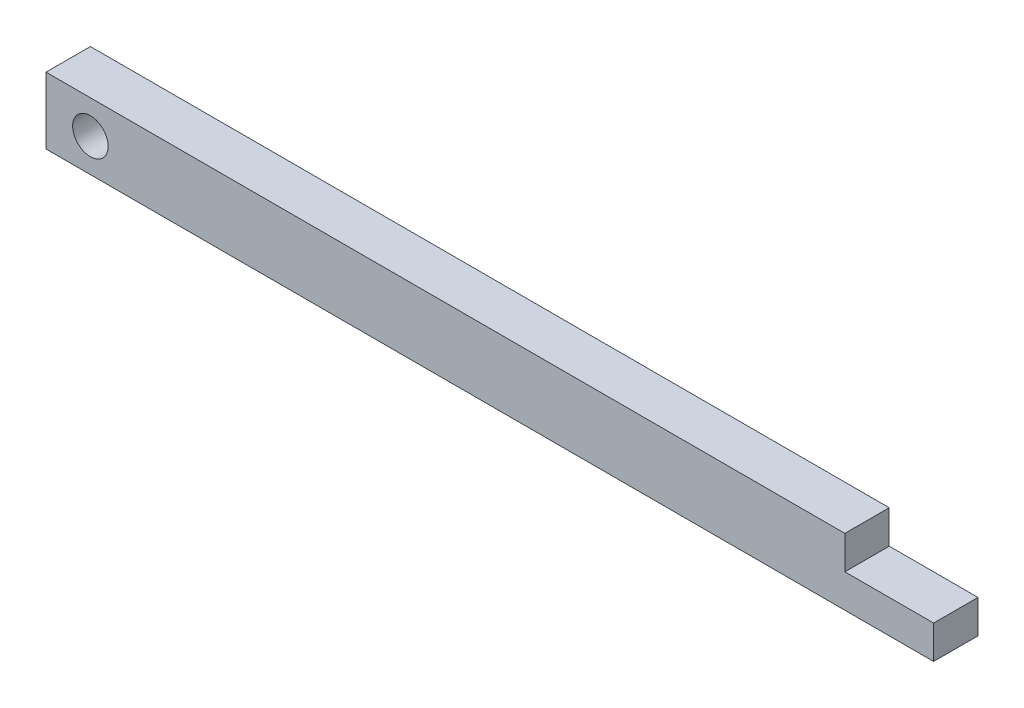
SolidWorks part; units mm, degrees
ref_plane "Front Plane" through (0, 0, 0) normal (0, 0, 1) x (1, 0, 0)
ref_plane "Top Plane" through (0, 0, 0) normal (0, 1, 0) x (1, 0, 0)
ref_plane "Right Plane" through (0, 0, 0) normal (1, 0, 0) x (0, 0, -1)
sketch "Sketch1" plane through (0, 0, 0) normal (0, 0, 1) x (1, 0, 0)
  line L0 (200, 7.5) -> (180, 7.5)
  line L1 (0, 0) -> (200, 0)
  line L2 (0, 0) -> (0, 15)
  line L3 (0, 15) -> (180, 15)
  line L4 (200, 0) -> (200, 7.5)
  line L5 (180, 7.5) -> (180, 15)
  circle A0 centre (10, 7.5) radius 3.1785
  point P9 (0, 7.5)
  dimension "D1" = 15
  dimension "D2" = 200
  dimension "D3" = 10
  dimension "D4" = 7.5
  dimension "D5" = 7.5
  dimension "D6" = 20
extrude "Boss-Extrude1" add sketch "Sketch1" along normal blind 10 contours L3 L5 L0 L4 L1 L2
sketch "Sketch3" plane through (0, 0, 10) normal (0, 0, 1) x (1, 0, 0)
  line L0 (0, 0) -> (200, 0) construction
  line L1 (0, 0) -> (0, 15) construction
  circle A0 centre (10, 7.5) radius 4
  dimension "D1" = 8
  dimension "D2" = 10
  dimension "7.5" = 7.5
extrude "Cut-Extrude1" cut sketch "Sketch3" against normal blind 10
